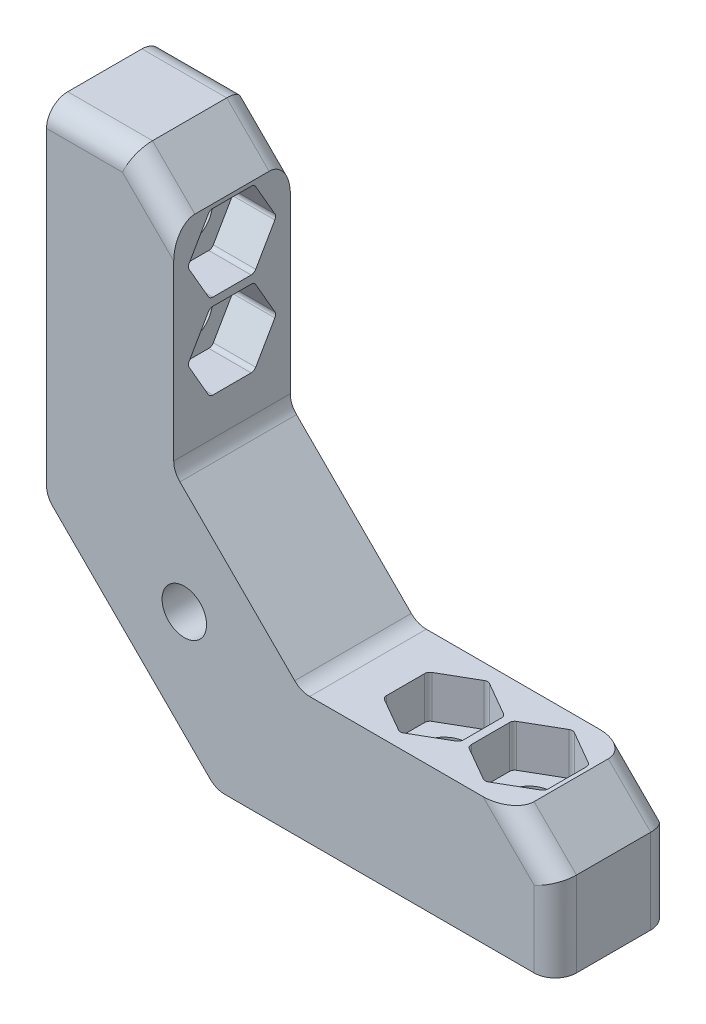
SolidWorks part; units mm, degrees
material "ABS"
ref_plane "前视基准面" through (0, 0, 0) normal (0, 0, 1) x (1, 0, 0)
ref_plane "上视基准面" through (0, 0, 0) normal (0, 1, 0) x (1, 0, 0)
ref_plane "右视基准面" through (0, 0, 0) normal (1, 0, 0) x (0, 0, -1)
other "Configuration Table"
sketch "草图1" plane through (0, 0, 0) normal (0, 0, 1) x (1, 0, 0)
  line L0 (0, 0) -> (48, 0)
  line L1 (48, 0) -> (48, 12)
  line L2 (48, 12) -> (24, 12)
  line L3 (24, 12) -> (12, 24)
  line L4 (12, 24) -> (12, 48)
  line L5 (12, 48) -> (0, 48)
  line L6 (0, 48) -> (0, 0)
  line L7 (0, 16) -> (16, 0)
  dimension "D1" = 12
  dimension "D2" = 12
  dimension "D3" = 48
  dimension "D4" = 48
  dimension "D5" = 16
  dimension "D6" = 24
extrude "凸台-拉伸1" add sketch "草图1" along normal blind 11 contours L6 L7 L0 L1 L2 L3 L4 L5
sketch "草图2" plane through (0, 0, 0) normal (-1, 0, 0) x (0, 0, 1)
  line L0 (5.5, 40) -> (5.5, 48) construction
  line L1 (11, 48) -> (0, 48) construction
  circle A0 centre (5.5, 40) radius 2.15
  circle A1 centre (5.5, 32) radius 2.15
  dimension "D1" = 8
  dimension "D2" = 4.3
  dimension "D3" = 2
extrude "切除-拉伸1" cut sketch "草图2" against normal through all both
sketch "草图3" plane through (12, 0, 0) normal (1, 0, 0) x (0, 0, -1)
  line L1 (-1.3142, 40) -> (-3.4071, 43.625)
  line L2 (-3.4071, 43.625) -> (-7.5929, 43.625)
  line L3 (-7.5929, 43.625) -> (-9.6858, 40)
  line L4 (-9.6858, 40) -> (-7.5929, 36.375)
  line L5 (-7.5929, 36.375) -> (-3.4071, 36.375)
  line L6 (-3.4071, 36.375) -> (-1.3142, 40)
  line L7 (-1.3142, 32) -> (-3.4071, 35.625)
  line L8 (-3.4071, 35.625) -> (-7.5929, 35.625)
  line L9 (-7.5929, 35.625) -> (-9.6858, 32)
  line L10 (-9.6858, 32) -> (-7.5929, 28.375)
  line L11 (-7.5929, 28.375) -> (-3.4071, 28.375)
  line L12 (-3.4071, 28.375) -> (-1.3142, 32)
  circle A0 centre (-5.5, 40) radius 3.625 construction
  circle A1 centre (-5.5, 32) radius 3.625 construction
  dimension "D1" = 7.25
  dimension "D2" = 7.25
extrude "切除-拉伸2" cut sketch "草图3" against normal blind 4
ref_plane "基准面1" through (0, 0, 0) normal (-0.7071, 0.7071, 0) x (0.7071, 0.7071, 0)
mirror "镜向1" about plane through (0, 0, 0) normal (-0.7071, 0.7071, 0) of "切除-拉伸2", "切除-拉伸1"
fillet "圆角1" radius 2 4 edges at (0, 16, 5.5) (16, 0, 5.5) (24, 12, 5.5) (12, 24, 5.5)
chamfer "倒角1" distance 4 angle 45 2 edges at (48, 12, 5.5) (12, 48, 5.5)
fillet "圆角2" radius 2 8 edges at (48, 4, 0) (48, 4, 11) (4, 48, 0) (4, 48, 11) (46, 10, 11) (46, 10, 0) (10, 46, 0) (10, 46, 11)
fillet "圆角3" radius 0.5 24 edges at (10, 35.625, 3.4071) (10, 35.625, 7.5929) (10, 32, 9.6858) (10, 28.375, 7.5929) (10, 28.375, 3.4071) (10, 32, 1.3142) (10, 43.625, 3.4071) (10, 43.625, 7.5929) (10, 40, 9.6858) (10, 36.375, 7.5929) (10, 40, 1.3142) (10, 36.375, 3.4071) (36.375, 10, 3.4071) (36.375, 10, 7.5929) (40, 10, 9.6858) (43.625, 10, 7.5929) (43.625, 10, 3.4071) (40, 10, 1.3142) (28.375, 10, 3.4071) (28.375, 10, 7.5929) (32, 10, 9.6858) (35.625, 10, 7.5929) (35.625, 10, 3.4071) (32, 10, 1.3142)
sketch "草图4" plane through (0, 0, 11) normal (0, 0, 1) x (1, 0, 0)
  line L0 (18, 18) -> (8, 8) construction
  line L2 (23.4142, 12.5858) -> (12.5858, 23.4142) construction
  line L3 (0.5858, 15.4142) -> (15.4142, 0.5858) construction
  circle A0 centre (13, 13) radius 2.1
  dimension "D1" = 4.2
extrude "切除-拉伸3" cut sketch "草图4" against normal through all
